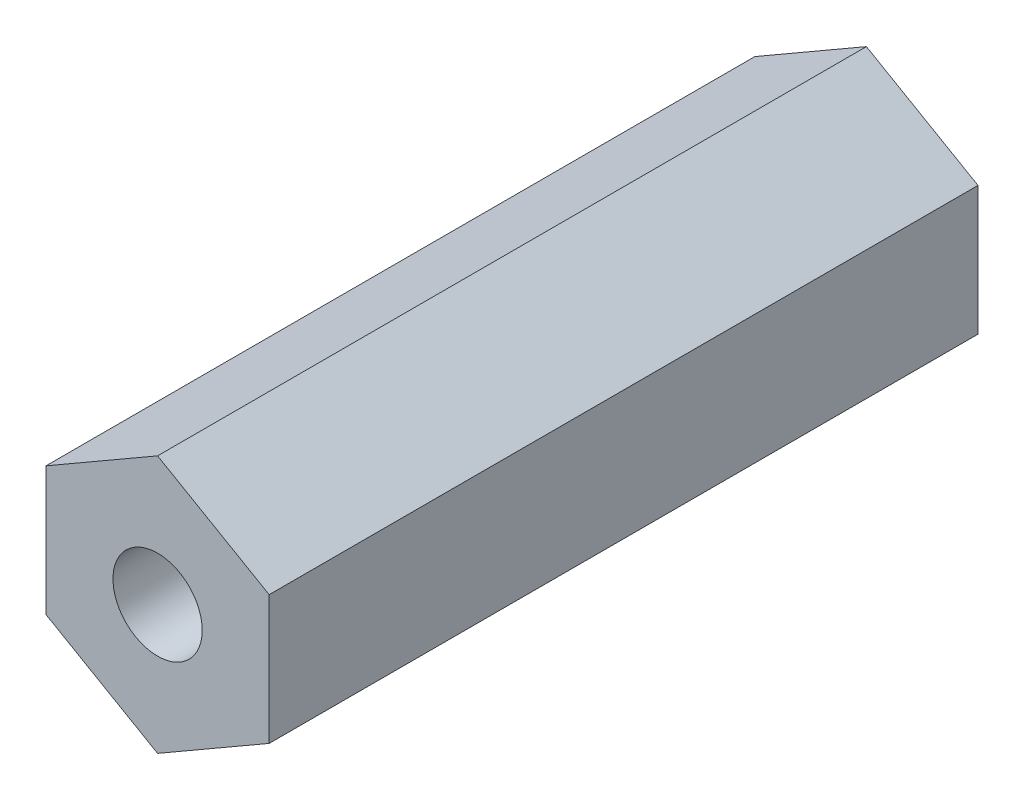
SolidWorks part; units mm, degrees
ref_plane "Front Plane" through (0, 0, 0) normal (0, 0, 1) x (1, 0, 0)
ref_plane "Top Plane" through (0, 0, 0) normal (0, 1, 0) x (1, 0, 0)
ref_plane "Right Plane" through (0, 0, 0) normal (1, 0, 0) x (0, 0, -1)
sketch "Sketch1" plane through (0, 0, 0) normal (0, 0, 1) x (1, 0, 0)
  line L1 (6.35, 3.6662) -> (0, 7.3323)
  line L2 (0, 7.3323) -> (-6.35, 3.6662)
  line L3 (-6.35, 3.6662) -> (-6.35, -3.6662)
  line L4 (-6.35, -3.6662) -> (0, -7.3323)
  line L5 (0, -7.3323) -> (6.35, -3.6662)
  line L6 (6.35, -3.6662) -> (6.35, 3.6662)
  circle A0 centre (0, 0) radius 6.35 construction
  dimension "D1" = 12.7
extrude "Boss-Extrude1" add sketch "Sketch1" along normal mid plane 40.34 contours L2 L3 L4 L5 L6 L1
sketch "Sketch2" plane through (0, 0, 20.17) normal (0, 0, 1) x (1, 0, 0)
  circle A0 centre (0, 0) radius 2.54
  dimension "D1" = 5.08
extrude "Cut-Extrude1" cut sketch "Sketch2" against normal through all
